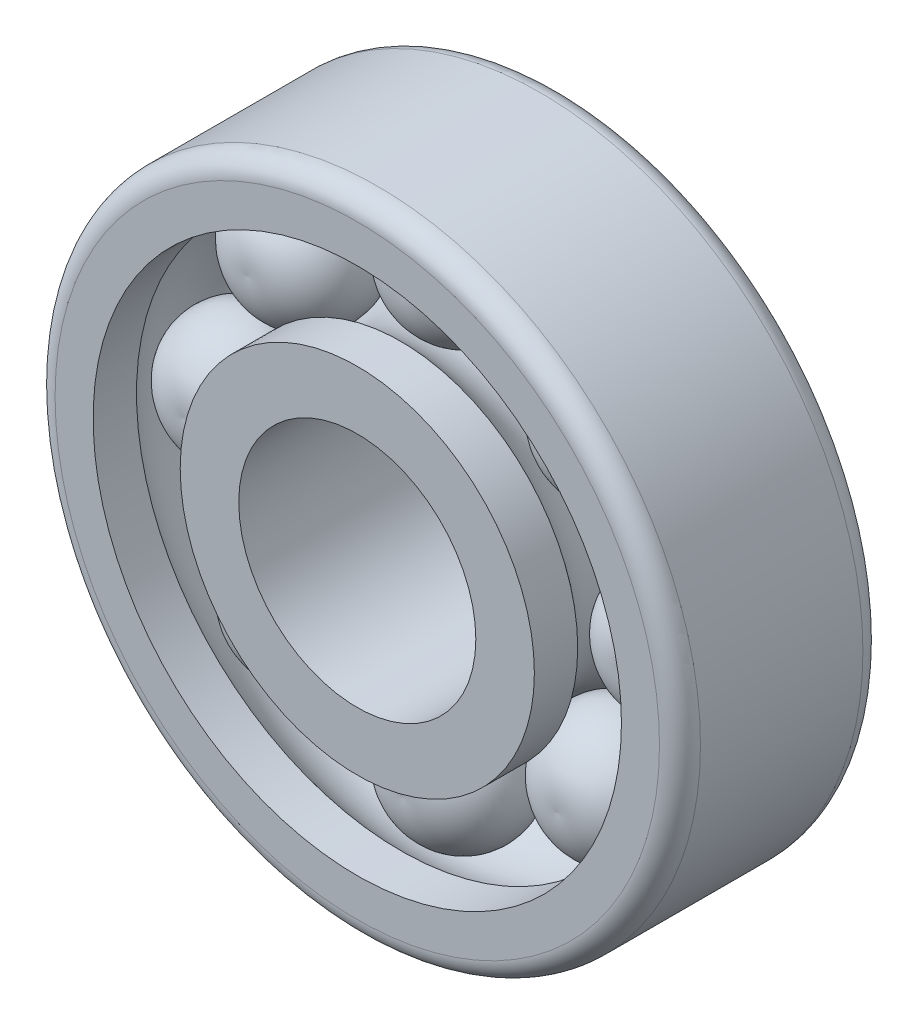
SolidWorks part; units mm, degrees
material "Alloy Steel"
ref_plane "Front Plane" through (0, 0, 0) normal (0, 0, 1) x (1, 0, 0)
ref_plane "Top Plane" through (0, 0, 0) normal (0, 1, 0) x (1, 0, 0)
ref_plane "Right Plane" through (0, 0, 0) normal (1, 0, 0) x (0, 0, -1)
sketch "Croquis5" plane through (0, 0, 0) normal (0, 1, 0) x (1, 0, 0)
  line L0 (0, 0) -> (0, 5.384) construction
sketch "Croquis3" plane through (0, 0, 0) normal (0, 1, 0) x (1, 0, 0)
  line L0 (-11.025, -3.475) -> (-4.05, 3.475) construction
  line L1 (-9.025, 3.475) -> (-11.025, 3.475)
  line L2 (-9.025, 3.475) -> (-9.025, 1.9937)
  line L3 (-9.025, -3.475) -> (-11.025, -3.475)
  line L4 (-11.025, 3.475) -> (-11.025, -3.475)
  line L5 (-9.025, 3.475) -> (-11.025, -3.475) construction
  line L6 (-9.025, -3.475) -> (-11.025, 3.475) construction
  line L7 (-6.05, 3.475) -> (-4.05, 3.475)
  line L8 (-6.05, 3.475) -> (-6.05, 1.9937)
  line L9 (-6.05, -3.475) -> (-4.05, -3.475)
  line L10 (-4.05, 3.475) -> (-4.05, -3.475)
  line L11 (-6.05, 3.475) -> (-4.05, -3.475) construction
  line L12 (-6.05, -3.475) -> (-4.05, 3.475) construction
  line L13 (-9.025, -1.9937) -> (-9.025, -3.475)
  line L14 (-6.05, -1.9937) -> (-6.05, -3.475)
  arc A0 (-9.025, 1.9937) -> (-9.025, -1.9937) centre (-7.5375, 0) ccw
  arc A1 (-6.05, -1.9937) -> (-6.05, 1.9937) centre (-7.5375, 0) ccw
  point P0 (-10.025, 0)
  point P5 (-5.05, 0)
  dimension "D1" = 4.05
  dimension "D2" = 11.025
  dimension "D3" = 2
  dimension "D4" = 6.95
sketch "Croquis4" plane through (0, 0, 0) normal (0, 1, 0) x (1, 0, 0)
  line L0 (-7.4875, 2.0149) -> (-7.4875, -1.9373)
  arc A0 (-7.4875, 2.0149) -> (-7.4875, -1.9373) centre (-7.237, 0.0388) cw
revolve "Revolución3" add sketch "Croquis4" angle 360 about L0
revolve "Revolución4" add sketch "Croquis3" angle 360 about L0
pattern_circular "MatrizC4" count 8 over 360 about axis through (0, 0, 0) along (0, 0, 1) of bodies 139
fillet "Redondeo1" radius 0.7 2 edges at (11.025, 0, 3.475) (11.025, 0, -3.475)
